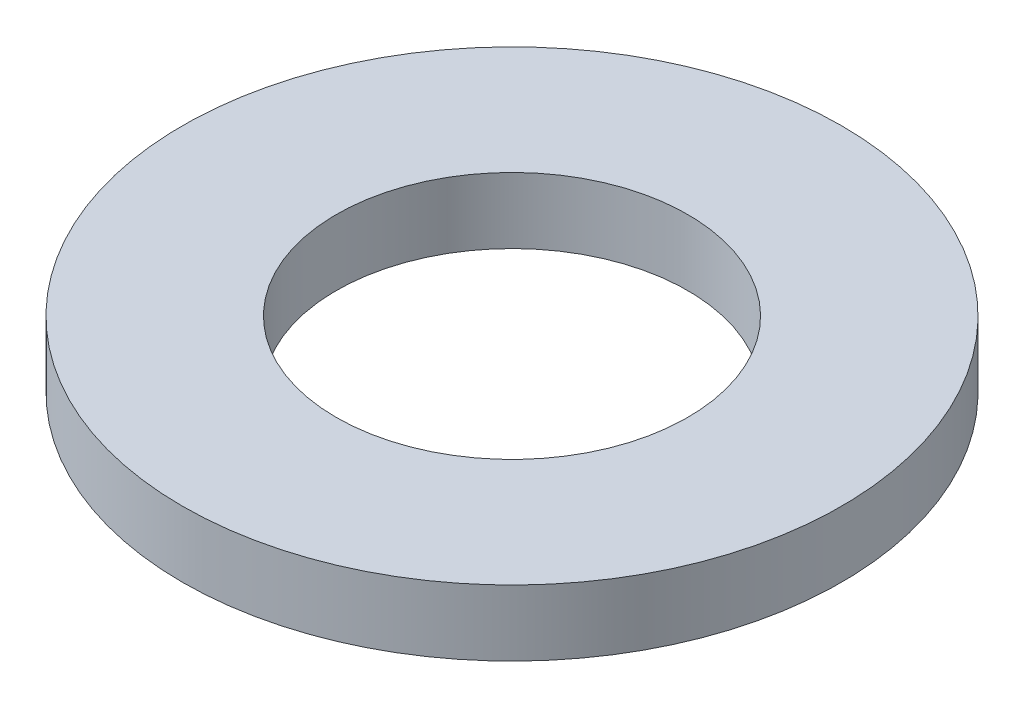
SolidWorks part; units mm, degrees
ref_plane "Front Plane" through (0, 0, 0) normal (0, 0, 1) x (1, 0, 0)
ref_plane "Top Plane" through (0, 0, 0) normal (0, 1, 0) x (1, 0, 0)
ref_plane "Right Plane" through (0, 0, 0) normal (1, 0, 0) x (0, 0, -1)
sketch "Sketch1" plane through (0, 0, 0) normal (0, 1, 0) x (1, 0, 0)
  circle A0 centre (0, 0) radius 4
  circle A1 centre (0, 0) radius 7.5
  dimension "D1" = 8
  dimension "D2" = 15
extrude "Boss-Extrude1" add sketch "Sketch1" along normal blind 1.5
